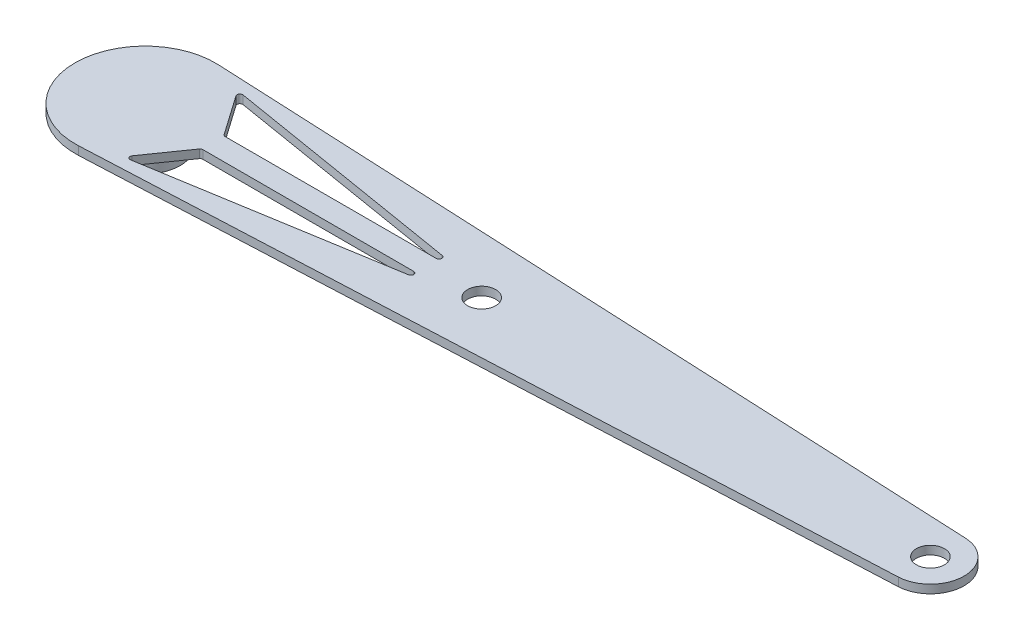
SolidWorks part; units mm, degrees
ref_plane "前视基准面" through (0, 0, 0) normal (0, 0, 1) x (1, 0, 0)
ref_plane "上视基准面" through (0, 0, 0) normal (0, 1, 0) x (1, 0, 0)
ref_plane "右视基准面" through (0, 0, 0) normal (1, 0, 0) x (0, 0, -1)
other "Configuration Table"
sketch "草图1" plane through (0, 0, 0) normal (0, 1, 0) x (1, 0, 0)
  circle A0 centre (0, 0) radius 3
  circle A1 centre (0, 0) radius 12.5
  dimension "D1" = 6
  dimension "D2" = 25
extrude "凸台-拉伸1" add sketch "草图1" along normal blind 10 contours A0 | A1
sketch "草图2" plane through (0, 0, 0) normal (0, 0, 1) x (1, 0, 0)
  line L0 (12.5, 0) -> (12.5, 10) construction
  line L1 (-12.5, 10) -> (-12.5, 0) construction
  line L2 (-12.5, 0) -> (12.5, 0) construction
  line L3 (12.5, 10) -> (-12.5, 10) construction
  line L4 (12.5, 0) -> (12.5, 10) construction
  line L5 (-12.5, 10) -> (-12.5, 0) construction
  line L6 (-12.5, 0) -> (12.5, 0) construction
  line L7 (12.5, 10) -> (-12.5, 10) construction
  circle A0 centre (0, 5) radius 1.6
  point P7 (12.5, 5)
  dimension "D1" = 3.2
extrude "切除-拉伸4" cut sketch "草图2" against normal mid plane 25
sketch "草图3" plane through (0, 10, 0) normal (0, 1, 0) x (1, 0, 0)
  line L0 (1.1607, 24.973) -> (280.5571, 11.9871)
  line L1 (1.1607, -24.973) -> (280.5571, -11.9871)
  circle A0 centre (0, 0) radius 12.5 construction
  circle A1 centre (0, 0) radius 12.5 construction
  circle A2 centre (280, 0) radius 5
  circle A3 centre (120, 0) radius 5
  arc A5 (280.5571, -11.9871) -> (280.5571, 11.9871) centre (280, 0) ccw
  arc A6 (1.1607, -24.973) -> (1.1607, 24.973) centre (0, 0) cw
  dimension "D1" = 10
  dimension "D3" = 120
  dimension "D4" = 25
  dimension "D5" = 10
  dimension "D6" = 12
  dimension "D2" = 280
extrude "凸台-拉伸2" add sketch "草图3" along normal blind 3 contours L0 A5 L1 A6 | A3 | A2
sketch "草图4" plane through (0, 10, 0) normal (0, -1, 0) x (1, 0, 0)
  line L2 (1.1607, -24.973) -> (280.5571, -11.9871)
  line L3 (280.5571, 11.9871) -> (1.1607, 24.973)
  line L4 (1.1607, -24.973) -> (280.5571, -11.9871) construction
  line L5 (280.5571, 11.9871) -> (1.1607, 24.973) construction
  circle A0 centre (0, 0) radius 12.5 construction
  circle A1 centre (0, 0) radius 12.5 construction
  circle A2 centre (0, 0) radius 18
  arc A4 (1.1607, 24.973) -> (1.1607, -24.973) centre (0, 0) ccw
  arc A5 (280.5571, -11.9871) -> (280.5571, 11.9871) centre (280, 0) ccw
  arc A6 (1.1607, 24.973) -> (1.1607, -24.973) centre (0, 0) ccw construction
  arc A7 (280.5571, -11.9871) -> (280.5571, 11.9871) centre (280, 0) ccw construction
  dimension "D2" = 36
  dimension "D1" = 0
extrude "凸台-拉伸3" add sketch "草图4" along normal blind 2.5
fillet "圆角1" radius 1 1 edges at (0, 7.5, -18)
sketch "草图5" plane through (0, 10, 0) normal (0, -1, 0) x (1, 0, 0)
  line L1 (24.0562, 4) -> (111.9377, 4)
  line L4 (0, 0) -> (280, 0) construction
  line L5 (0, -4) -> (280, -4) construction
  line L6 (0.975, -20.9774) -> (280.3714, -7.9914)
  line L7 (280.3714, 7.9914) -> (0.975, 20.9774)
  line L8 (0.975, -20.9774) -> (280.3714, -7.9914) construction
  line L9 (280.3714, 7.9914) -> (0.975, 20.9774) construction
  line L10 (0, 4) -> (280, 4) construction
  line L13 (12.5451, 20.4396) -> (24.0562, 4)
  line L14 (12.5451, 20.4396) -> (111.9377, 4)
  line L15 (12.5451, -20.4396) -> (24.0562, -4)
  line L16 (24.0562, -4) -> (111.9377, -4)
  line L17 (12.5451, -20.4396) -> (111.9377, -4)
  circle A0 centre (120, 0) radius 5 construction
  circle A1 centre (120, 0) radius 5 construction
  circle A2 centre (0, 0) radius 18 construction
  circle A3 centre (0, 0) radius 18 construction
  circle A4 centre (120, 0) radius 9 construction
  circle A5 centre (120, 0) radius 1
  arc A6 (0.975, 20.9774) -> (0.975, -20.9774) centre (0, 0) ccw
  arc A7 (280.3714, -7.9914) -> (280.3714, 7.9914) centre (280, 0) ccw
  arc A8 (0.975, 20.9774) -> (0.975, -20.9774) centre (0, 0) ccw construction
  arc A9 (280.3714, -7.9914) -> (280.3714, 7.9914) centre (280, 0) ccw construction
  circle A10 centre (0, 0) radius 22 construction
  point P4 (18.1332, 20.9774)
  point P5 (0, 0)
  point P8 (0.975, 20.9774)
  point P11 (0, 0)
  point P12 (0, 0)
  point P13 (24.0422, 4)
  point P18 (0, 0)
  dimension "D6" = 4
  dimension "D7" = 125
  dimension "D2" = 4
  dimension "D4" = 4
  dimension "D5" = 4
  dimension "D1" = 4
  dimension "D3" = 4
extrude "切除-拉伸5" cut sketch "草图5" against normal up to surface (3 mm away) up to face at (137.1795, 13, 0)
fillet "圆角2" radius 1 6 edges at (24.0562, 11.5, 4) (111.9377, 11.5, 4) (12.5451, 11.5, 20.4396) (111.9377, 11.5, -4) (24.0562, 11.5, -4) (12.5451, 11.5, -20.4396)
